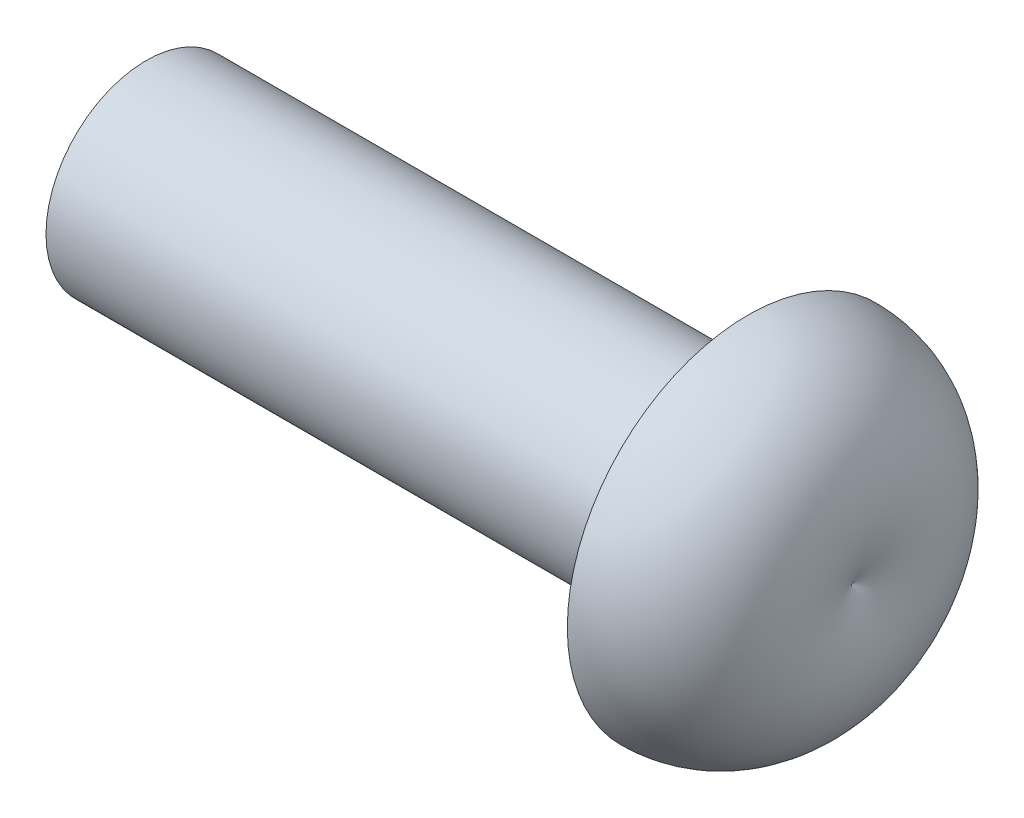
SolidWorks part; units mm, degrees
ref_plane "前视基准面" through (0, 0, 0) normal (0, 0, 1) x (1, 0, 0)
ref_plane "上视基准面" through (0, 0, 0) normal (0, 1, 0) x (1, 0, 0)
ref_plane "右视基准面" through (0, 0, 0) normal (1, 0, 0) x (0, 0, -1)
sketch "草图1" plane through (0, 0, 0) normal (0, 0, 1) x (1, 0, 0)
  line L0 (-15, 0) -> (0, 0)
  line L1 (0, 0) -> (0, 2)
  line L2 (-16.3869, -2.5) -> (9.8737, -2.5) construction
  line L3 (-15, -2.5) -> (2.5981, -2.5)
  line L4 (-15, 0) -> (-15, -2.5)
  arc A0 (0, 2) -> (2.5981, -2.5) centre (0, -1) cw
  dimension "D2" = 3
  dimension "D1" = 15
  dimension "D3" = 2
  dimension "D4" = 2.5
revolve "旋转1" add sketch "草图1" angle 360 about L2
